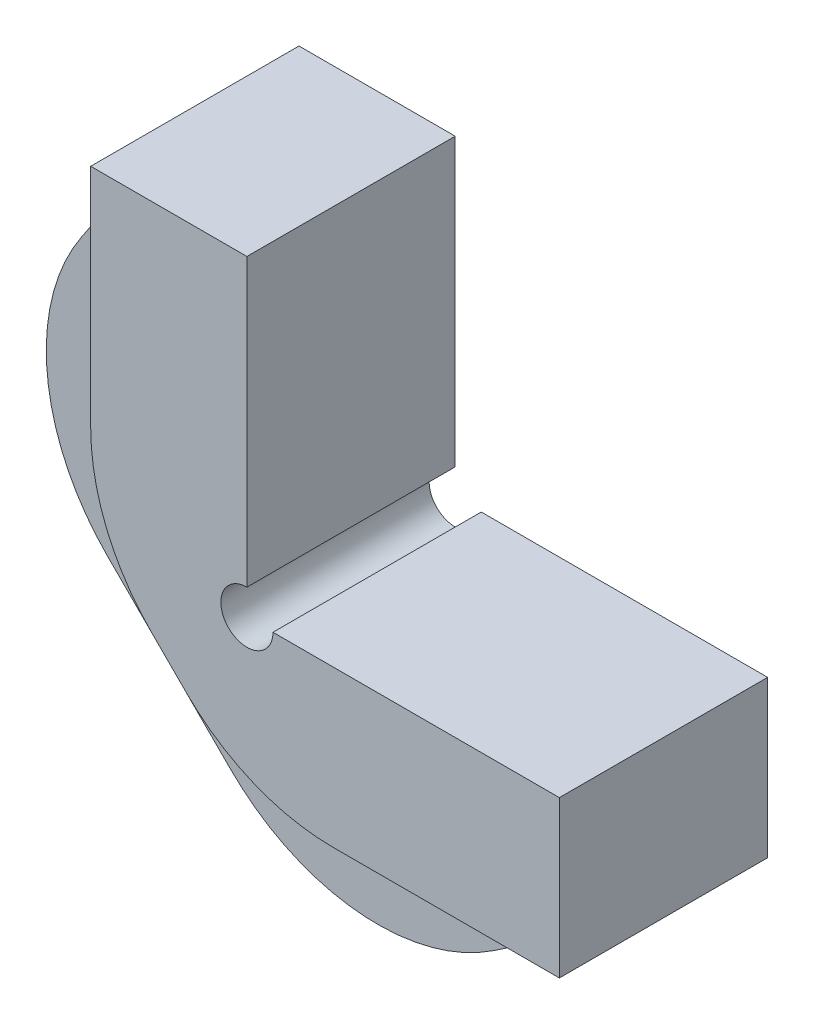
SolidWorks part; units mm, degrees
ref_plane "Piano frontale" through (0, 0, 0) normal (0, 0, 1) x (1, 0, 0)
ref_plane "Piano superiore" through (0, 0, 0) normal (0, 1, 0) x (1, 0, 0)
ref_plane "Piano destro" through (0, 0, 0) normal (1, 0, 0) x (0, 0, -1)
sketch "Schizzo1" plane through (0, 0, 0) normal (0, 0, 1) x (1, 0, 0)
  line L0 (-15, 0) -> (0, -15)
  line L1 (-15, 30) -> (0, 30)
  line L2 (-15, 30) -> (-15, 0)
  line L4 (0, 30) -> (0, 2.5)
  line L5 (2.5, 0) -> (30, 0)
  line L7 (0, -15) -> (30, -15)
  line L8 (30, 0) -> (30, -15)
  arc A0 (0, 2.5) -> (2.5, 0) centre (0, 0) ccw
  dimension "D3" = 5
  dimension "D1" = 30
  dimension "D2" = 15
extrude "Estrusione-Estrusione1" add sketch "Schizzo1" along normal blind 20
sketch "Schizzo2" plane through (0, 0, 0) normal (0, 0, -1) x (-1, 0, 0)
  line L0 (15, 30) -> (35, 0)
  line L1 (35, 0) -> (0, -35)
  line L2 (0, -35) -> (-30, -15)
  line L3 (15, 0) -> (35, 0)
  line L4 (0, -15) -> (0, -35)
  line L5 (15, 30) -> (15, 0) construction
  line L6 (0, -15) -> (-30, -15) construction
  dimension "D1" = 20
  dimension "D2" = 20
extrude "Estrusione-Estrusione3" add sketch "Schizzo2" against normal blind 10
sketch "Schizzo4" plane through (0, 0, 10) normal (0, 0, 1) x (1, 0, 0)
  line L0 (-7.5, -7.5) -> (-17.5, -17.5)
  line L1 (0, -15) -> (-15, 0) construction
  line L2 (-35, 0) -> (0, -35) construction
  circle A0 centre (-12.5, -12.5) radius 3
  dimension "D1" = 6
extrude "Taglio-Estrusione2" cut sketch "Schizzo4" against normal through all contours L0 A0 | L0 A0
chamfer "Smusso2" distance 3 angle 45 1 edges at (-9.5, -12.5, 10)
fillet "Raccordo3" radius 20 4 edges at (0, -15, 15) (-15, 0, 15) (-35, 0, 5) (0, -35, 5)
